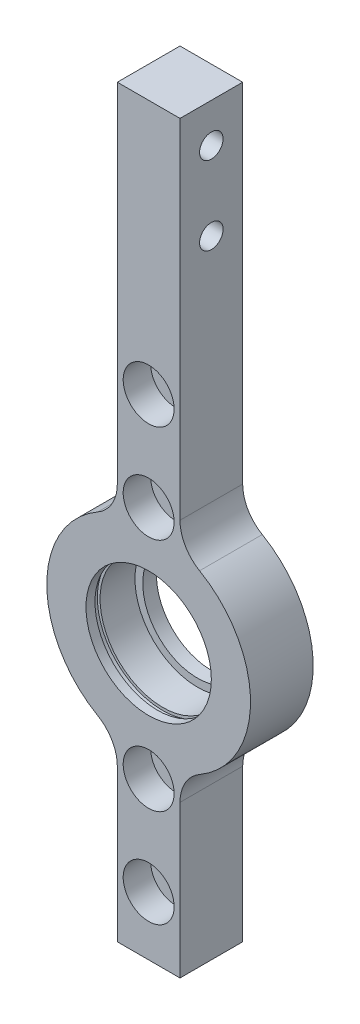
SolidWorks part; units mm, degrees
material "1060 Alloy"
ref_plane "Front Plane" through (0, 0, 0) normal (0, 0, 1) x (1, 0, 0)
ref_plane "Top Plane" through (0, 0, 0) normal (0, 1, 0) x (1, 0, 0)
ref_plane "Right Plane" through (0, 0, 0) normal (1, 0, 0) x (0, 0, -1)
sketch "Sketch1" plane through (0, 0, 0) normal (0, 0, 1) x (1, 0, 0)
  circle A0 centre (0, 0) radius 14
  circle A1 centre (0, 0) radius 26
  dimension "D1" = 28
  dimension "D2" = 52
extrude "Boss-Extrude1" add sketch "Sketch1" along normal mid plane 16
sketch "Sketch2" plane through (0, 0, 0) normal (0, 0, 1) x (1, 0, 0)
  line L0 (0, 0) -> (0, 74.602) construction
  line L1 (-8, 120) -> (8, 120)
  line L2 (8, 120) -> (8, 24.7386)
  line L3 (8, 24.7386) -> (0, 26)
  line L4 (-8, 24.7386) -> (0, 26)
  line L5 (-8, 120) -> (-8, 24.7386)
  circle A0 centre (0, 0) radius 26 construction
  point P11 (0, 120)
  dimension "D1" = 16
  dimension "D2" = 120
extrude "Boss-Extrude2" add sketch "Sketch2" along normal mid plane 16
sketch "Sketch3" plane through (0, 0, 0) normal (1, 0, 0) x (0, 0, -1)
  line L0 (0, 0) -> (53.684, 0) construction
  line L1 (4.5, 14) -> (4.5, 16)
  line L2 (8, 14) -> (-8, 14) construction
  line L3 (4.5, 16) -> (-8, 16)
  line L4 (-8, 24.7386) -> (-8, -26) construction
  line L5 (-8, 16) -> (-8, 14)
  line L6 (-8, 14) -> (4.5, 14)
  dimension "D1" = 16
  dimension "D2" = 4.5
revolve "Cut-Revolve1" cut sketch "Sketch3" angle 360 about L0
sketch "Sketch4" plane through (0, 0, 0) normal (1, 0, 0) x (0, 0, -1)
  line L0 (0, 0) -> (21.5903, 0) construction
  line L1 (-4.4, 16) -> (-4.4, 16.7)
  line L2 (-4.4, 16.7) -> (-5.7, 16.7)
  line L3 (-5.7, 16.7) -> (-5.7, 16)
  line L4 (-5.7, 16) -> (-4.4, 16)
  line L5 (4.5, 16) -> (4.5, -16) construction
  dimension "D1" = 10.2
  dimension "D2" = 1.3
  dimension "D3" = 16.7
  dimension "D4" = 16
revolve "Cut-Revolve2" cut sketch "Sketch4" angle 360 about L0
sketch "Sketch5" plane through (0, 0, 0) normal (0, 0, 1) x (1, 0, 0)
  line L0 (0, -26) -> (0, -97.142) construction
  line L1 (-8, -24.7386) -> (-8, -70)
  line L2 (-8, -70) -> (8, -70)
  line L3 (8, -24.7386) -> (8, -70)
  line L4 (8, -24.7386) -> (-8, -24.7386)
  arc A0 (-8, 24.7386) -> (8, 24.7386) centre (0, 0) ccw construction
  point P11 (0, -70)
  dimension "D1" = 16
  dimension "D2" = 70
extrude "Boss-Extrude3" add sketch "Sketch5" along normal mid plane 16
fillet "Fillet1" radius 10 4 edges at (-8, -24.7386, 0) (8, -24.7386, 0) (8, 24.7386, 0) (-8, 24.7386, 0)
sketch "Sketch6" plane through (-8, 0, 0) normal (-1, 0, 0) x (0, 0, 1)
  line L0 (0, 24.8728) -> (0, 126.365) construction
  line L1 (8, 120) -> (-8, 120) construction
  circle A0 centre (0, 110) radius 3
  circle A1 centre (0, 90) radius 3
  dimension "D1" = 6
  dimension "D2" = 6
  dimension "D4" = 20
  dimension "D3" = 10
extrude "Cut-Extrude1" cut sketch "Sketch6" against normal through all
sketch "Sketch9" plane through (0, 0, 8) normal (0, 0, 1) x (1, 0, 0)
  line L0 (0, 0) -> (0, -80.6152) construction
  line L1 (-8, -70) -> (8, -70) construction
  circle A0 centre (0, -55) radius 6.5
  circle A1 centre (0, -30) radius 6.5
  dimension "D1" = 13
  dimension "D2" = 13
  dimension "D3" = 15
  dimension "D4" = 25
extrude "Cut-Extrude4" cut sketch "Sketch9" against normal blind 7
sketch "Sketch10" plane through (0, 0, 8) normal (0, 0, 1) x (1, 0, 0)
  circle A0 centre (0, -30) radius 3
  circle A1 centre (0, -55) radius 3
  dimension "D1" = 6
  dimension "D2" = 6
extrude "Cut-Extrude5" cut sketch "Sketch10" against normal through all
mirror "Mirror1" about plane through (0, 0, 0) normal (0, 1, 0) of "Cut-Extrude4"
mirror "Mirror2" about plane through (0, 0, 0) normal (0, 1, 0) of "Cut-Extrude5"
